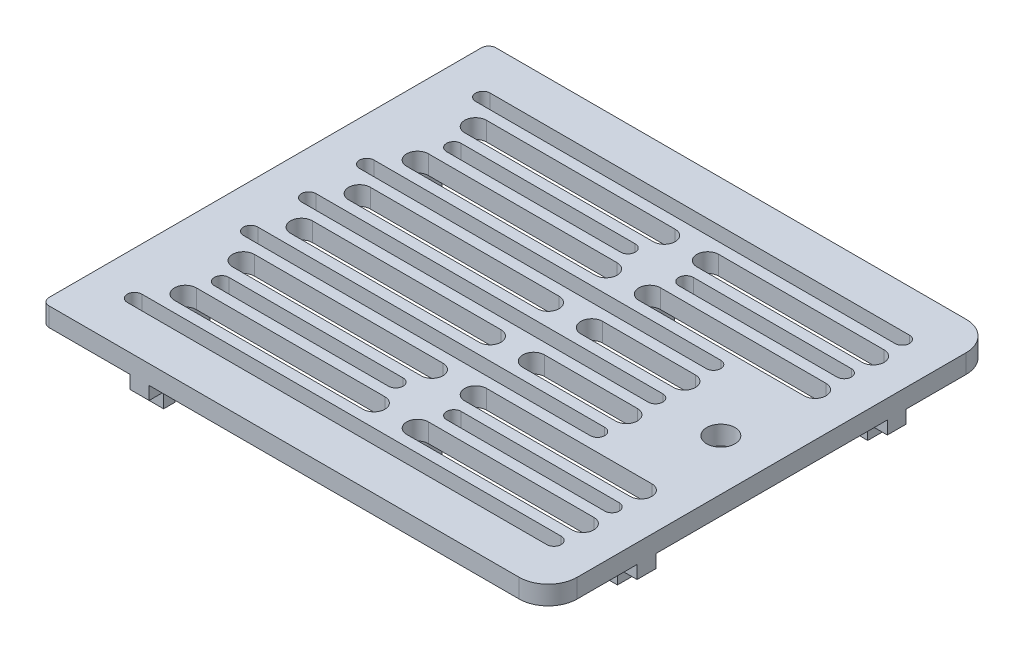
SolidWorks part; units mm, degrees
ref_plane "Front Plane" through (0, 0, 0) normal (0, 0, 1) x (1, 0, 0)
ref_plane "Top Plane" through (0, 0, 0) normal (0, 1, 0) x (1, 0, 0)
ref_plane "Right Plane" through (0, 0, 0) normal (1, 0, 0) x (0, 0, -1)
sketch "Sketch1" plane through (0, 0, 0) normal (0, 1, 0) x (1, 0, 0)
  line L1 (-33.9, -30.8) -> (30.9, -30.8)
  line L2 (-34.9, -29.8) -> (-34.9, 29.8)
  line L3 (-33.9, 30.8) -> (30.9, 30.8)
  line L4 (34.9, -26.8) -> (34.9, 26.8)
  line L5 (-34.9, -30.8) -> (34.9, 30.8) construction
  line L6 (-34.9, 30.8) -> (34.9, -30.8) construction
  arc A0 (30.9, -30.8) -> (34.9, -26.8) centre (30.9, -26.8) ccw
  arc A1 (34.9, 26.8) -> (30.9, 30.8) centre (30.9, 26.8) ccw
  arc A2 (-34.9, -29.8) -> (-33.9, -30.8) centre (-33.9, -29.8) ccw
  arc A3 (-33.9, 30.8) -> (-34.9, 29.8) centre (-33.9, 29.8) ccw
  point P0 (0, 0)
  dimension "D1" = 4
  dimension "D4" = 1
  dimension "D2" = 61.6
  dimension "D3" = 69.8
extrude "Boss-Extrude1" add sketch "Sketch1" along normal blind 2.6
sketch "Sketch3" plane through (0, 0, 0) normal (0, -1, 0) x (1, 0, 0)
  line L0 (-34.9, 0) -> (34.9, 0) construction
  line L1 (-28.9, -16) -> (3.1, -16) construction
  line L2 (-28.9, -16) -> (-28.9, 16) construction
  line L3 (-28.9, 16) -> (3.1, 16) construction
  line L4 (3.1, -16) -> (3.1, 16) construction
  line L5 (-28.9, -16) -> (3.1, 16) construction
  line L6 (-28.9, 16) -> (3.1, -16) construction
  line L7 (-34.9, -29.8) -> (-34.9, 29.8) construction
  line L8 (34.9, 26.8) -> (34.9, -26.8) construction
  circle A0 centre (-28.9, 16) radius 1.7
  circle A1 centre (3.1, 16) radius 1.7
  circle A2 centre (-28.9, -16) radius 1.7
  circle A3 centre (3.1, -16) radius 1.7
  circle A4 centre (3.1, 16) radius 0.75
  circle A5 centre (-28.9, 16) radius 0.75
  circle A6 centre (-28.9, -16) radius 0.75
  circle A7 centre (3.1, -16) radius 0.75
  point P14 (-12.9, 0)
  point P20 (0, 0)
  point P21 (-11.73, 0.4922)
  dimension "D2" = 3.4
  dimension "D3" = 1.5
  dimension "D1" = 32
  dimension "D4" = 6
extrude "Boss-Extrude2" add sketch "Sketch3" along normal blind 4.4
sketch "Sketch2" plane through (0, 2.6, 0) normal (0, 1, 0) x (1, 0, 0)
  line L0 (-34.9, -20) -> (34.9, -20) construction
  line L3 (-34.9, 29.8) -> (-34.9, -29.8) construction
  line L4 (34.9, -26.8) -> (34.9, 26.8) construction
  line L6 (-34.9, 0) -> (34.9, 0) construction
  line L9 (28.9, -20) -> (6.1, -20) construction
  line L10 (28.9, -21.5) -> (6.1, -21.5)
  line L11 (28.9, -18.5) -> (6.1, -18.5)
  line L12 (0.1, -20) -> (-25.9, -20) construction
  line L13 (0.1, -21.5) -> (-25.9, -21.5)
  line L14 (0.1, -18.5) -> (-25.9, -18.5)
  arc A2 (28.9, -21.5) -> (28.9, -18.5) centre (28.9, -20) ccw
  arc A3 (6.1, -18.5) -> (6.1, -21.5) centre (6.1, -20) ccw
  arc A4 (0.1, -21.5) -> (0.1, -18.5) centre (0.1, -20) ccw
  arc A5 (-25.9, -18.5) -> (-25.9, -21.5) centre (-25.9, -20) ccw
  circle A6 centre (-28.9, -16) radius 0.75 construction
  circle A7 centre (-28.9, -16) radius 0.75 construction
  circle A8 centre (3.1, -16) radius 0.75 construction
  point P6 (-26.515, -24)
  point P7 (6.7269, -24)
  point P10 (28.5523, -24)
  point P11 (6.1, -21.8921)
  point P15 (17.5, -20)
  point P22 (-12.9, -20)
  point P29 (0, 0)
  point P35 (3.9847, -24)
  point P38 (-12.9, 0)
  dimension "D1" = 4
  dimension "D6" = 1.5
  dimension "D2" = 3
  dimension "D3" = 3
  dimension "D4" = 6
  dimension "D5" = 6
extrude "Cut-Extrude1" cut sketch "Sketch2" against normal through all
pattern_linear "LPattern1" count 6 spacing 8 along (0, 0, -1) of "Cut-Extrude1"
sketch "Sketch4" plane through (0, 0, 0) normal (0, -1, 0) x (1, 0, 0)
  line L0 (-34.9, 24) -> (34.9, 24) construction
  line L1 (-34.9, -29.8) -> (-34.9, 29.8) construction
  line L2 (34.9, 26.8) -> (34.9, -26.8) construction
  line L3 (-28.9, 24) -> (28.9, 24) construction
  line L4 (-28.9, 25) -> (28.9, 25)
  line L5 (-28.9, 23) -> (28.9, 23)
  line L6 (-28.9, 16) -> (34.9, 16) construction
  line L7 (-24.9, 16) -> (-0.9, 16) construction
  line L8 (-24.9, 17) -> (-0.9, 17)
  line L9 (-24.9, 15) -> (-0.9, 15)
  line L10 (7.1, 16) -> (28.9, 16) construction
  line L11 (7.1, 17) -> (28.9, 17)
  line L12 (7.1, 15) -> (28.9, 15)
  line L13 (-28.9, -16) -> (34.9, -16) construction
  line L14 (-24.9, -16) -> (-0.9, -16) construction
  line L15 (-24.9, -15) -> (-0.9, -15)
  line L16 (-24.9, -17) -> (-0.9, -17)
  line L17 (7.1, -16) -> (28.9, -16) construction
  line L18 (7.1, -15) -> (28.9, -15)
  line L19 (7.1, -17) -> (28.9, -17)
  line L20 (-34.9, -24) -> (34.9, -24) construction
  line L21 (-28.9, -24) -> (28.9, -24) construction
  line L22 (-28.9, -23) -> (28.9, -23)
  line L23 (-28.9, -25) -> (28.9, -25)
  line L24 (-28.9, 24) -> (-28.9, -24) construction
  line L25 (28.9, 24) -> (28.9, -24) construction
  line L26 (-28.9, 8) -> (18.9, 8) construction
  line L27 (-28.9, 9) -> (18.9, 9)
  line L28 (-28.9, 7) -> (18.9, 7)
  line L29 (18.9, 0) -> (-28.9, 0) construction
  line L30 (18.9, -1) -> (-28.9, -1)
  line L31 (18.9, 1) -> (-28.9, 1)
  line L32 (-28.9, -8) -> (18.9, -8) construction
  line L33 (-28.9, -7) -> (18.9, -7)
  line L34 (-28.9, -9) -> (18.9, -9)
  arc A0 (-25.9, 21.5) -> (-25.9, 18.5) centre (-25.9, 20) ccw construction
  arc A1 (-28.9, 25) -> (-28.9, 23) centre (-28.9, 24) ccw
  arc A2 (28.9, 23) -> (28.9, 25) centre (28.9, 24) ccw
  arc A3 (-28.9, 9) -> (-28.9, 7) centre (-28.9, 8) ccw
  arc A4 (-24.9, 17) -> (-24.9, 15) centre (-24.9, 16) ccw
  arc A5 (-0.9, 15) -> (-0.9, 17) centre (-0.9, 16) ccw
  arc A6 (7.1, 17) -> (7.1, 15) centre (7.1, 16) ccw
  arc A7 (28.9, 15) -> (28.9, 17) centre (28.9, 16) ccw
  circle A8 centre (3.1, 16) radius 0.75 construction
  arc A9 (-24.9, -15) -> (-24.9, -17) centre (-24.9, -16) ccw
  arc A10 (-0.9, -17) -> (-0.9, -15) centre (-0.9, -16) ccw
  arc A11 (7.1, -15) -> (7.1, -17) centre (7.1, -16) ccw
  arc A12 (28.9, -17) -> (28.9, -15) centre (28.9, -16) ccw
  arc A13 (-28.9, -23) -> (-28.9, -25) centre (-28.9, -24) ccw
  arc A14 (28.9, -25) -> (28.9, -23) centre (28.9, -24) ccw
  arc A15 (-25.9, -18.5) -> (-25.9, -21.5) centre (-25.9, -20) ccw construction
  arc A16 (18.9, 7) -> (18.9, 9) centre (18.9, 8) ccw
  arc A17 (18.9, -1) -> (18.9, 1) centre (18.9, 0) ccw
  arc A18 (-28.9, 1) -> (-28.9, -1) centre (-28.9, 0) ccw
  arc A19 (-28.9, -7) -> (-28.9, -9) centre (-28.9, -8) ccw
  arc A20 (18.9, -9) -> (18.9, -7) centre (18.9, -8) ccw
  arc A21 (-25.9, 13.5) -> (-25.9, 10.5) centre (-25.9, 12) ccw construction
  arc A22 (-25.9, -10.5) -> (-25.9, -13.5) centre (-25.9, -12) ccw construction
  circle A23 centre (27.9, 0) radius 1.95
  point P11 (0, 24)
  point P22 (-12.9, 16)
  point P27 (18, 16)
  point P42 (-12.9, -16)
  point P47 (18, -16)
  point P56 (0, -24)
  point P72 (-5, 8)
  point P77 (-5, 0)
  point P84 (-5, -8)
  point P97 (0, 0)
  point P98 (28.9, 0)
  point P99 (18.4041, -8)
  point P100 (18.4041, 8)
  point P103 (-5, 0)
  dimension "D2" = 1
  dimension "D5" = 4
  dimension "D7" = 1
  dimension "D9" = 4
  dimension "D10" = 4
  dimension "D11" = 3.9
  dimension "D1" = 4
  dimension "D3" = 6
  dimension "D4" = 4
  dimension "D6" = 4
  dimension "D8" = 4
  dimension "D12" = 9
  dimension "D13" = 1
extrude "Cut-Extrude2" cut sketch "Sketch4" against normal through all
sketch "Sketch6" plane through (0, 0, 0) normal (0, -1, 0) x (1, 0, 0)
  line L0 (-22.7, 27.2) -> (-22.7, -27.2) construction
  line L1 (-22.7, 30.8) -> (-20.1, 30.8)
  line L2 (-22.7, 30.8) -> (-22.7, 27.2)
  line L3 (-22.7, 27.2) -> (-20.1, 27.2)
  line L4 (-20.1, 30.8) -> (-20.1, 27.2)
  line L5 (-22.7, -27.2) -> (-20.1, -27.2)
  line L6 (-22.7, -27.2) -> (-22.7, -30.8)
  line L7 (-22.7, -30.8) -> (-20.1, -30.8)
  line L8 (-20.1, -27.2) -> (-20.1, -30.8)
  line L9 (34.9, 18.55) -> (30.6, 18.55)
  line L10 (34.9, 18.55) -> (34.9, 15.95)
  line L11 (34.9, 15.95) -> (30.6, 15.95)
  line L12 (30.6, 18.55) -> (30.6, 15.95)
  line L13 (34.9, -15.95) -> (30.6, -15.95)
  line L14 (34.9, -15.95) -> (34.9, -18.55)
  line L15 (34.9, -18.55) -> (30.6, -18.55)
  line L16 (30.6, -15.95) -> (30.6, -18.55)
  line L17 (-34.9, 0) -> (34.9, 0) construction
  line L18 (-34.9, -29.8) -> (-34.9, 29.8) construction
  line L20 (-33.9, 30.8) -> (30.9, 30.8) construction
  line L21 (30.9, -30.8) -> (-33.9, -30.8) construction
  line L22 (34.9, 26.8) -> (34.9, -26.8) construction
  line L23 (34.9, 26.8) -> (34.9, -26.8) construction
  line L24 (30.6, 15.95) -> (30.6, -15.95) construction
  point P22 (-22.7, 0)
  point P23 (30.6, 0)
  point P24 (0, 0)
  dimension "D1" = 54.4
  dimension "D2" = 2.6
  dimension "D3" = 12.2
  dimension "D4" = 31.9
  dimension "D5" = 4.3
extrude "Boss-Extrude4" add sketch "Sketch6" along normal blind 1.8
sketch "Sketch7" plane through (0, -1.8, 0) normal (0, -1, 0) x (1, 0, 0)
  line L0 (-20.1, 27.2) -> (-20.1, 30.8) construction
  line L1 (-22.7, 27.2) -> (-20.1, 27.2)
  line L2 (-22.7, 27.2) -> (-22.7, 28.8)
  line L3 (-22.7, 28.8) -> (-20.1, 28.8)
  line L4 (-20.1, 27.2) -> (-20.1, 28.8)
  line L5 (30.6, 15.95) -> (34.9, 15.95) construction
  line L6 (30.6, 18.55) -> (32.2, 18.55)
  line L7 (30.6, 18.55) -> (30.6, 15.95)
  line L8 (30.6, 15.95) -> (32.2, 15.95)
  line L9 (32.2, 18.55) -> (32.2, 15.95)
  line L10 (30.6, -18.55) -> (34.9, -18.55) construction
  line L11 (30.6, -15.95) -> (32.2, -15.95)
  line L12 (30.6, -15.95) -> (30.6, -18.55)
  line L13 (30.6, -18.55) -> (32.2, -18.55)
  line L14 (32.2, -15.95) -> (32.2, -18.55)
  line L16 (-20.1, -27.2) -> (-22.7, -27.2)
  line L17 (-20.1, -27.2) -> (-20.1, -28.8)
  line L18 (-20.1, -28.8) -> (-22.7, -28.8)
  line L19 (-22.7, -27.2) -> (-22.7, -28.8)
  line L20 (-22.7, -27.2) -> (-22.7, -30.8) construction
  point P26 (-22.7, -28.1642)
  dimension "D1" = 1.6
extrude "Boss-Extrude5" add sketch "Sketch7" along normal blind 2
sketch "Sketch8" plane through (0, 0, 0) normal (0, -1, 0) x (1, 0, 0)
  line L0 (28.9, -5.5) -> (6.1, -5.5) construction
  line L1 (6.1, -2.5) -> (28.9, -2.5) construction
  line L2 (28.9, 2.5) -> (6.1, 2.5) construction
  line L3 (6.1, 5.5) -> (28.9, 5.5) construction
  line L4 (28.9, -5.5) -> (18.9, -5.5)
  line L5 (18.9, -2.5) -> (28.9, -2.5)
  line L6 (28.9, 2.5) -> (18.9, 2.5)
  line L7 (18.9, 5.5) -> (28.9, 5.5)
  arc A0 (28.9, -5.5) -> (28.9, -2.5) centre (28.9, -4) ccw construction
  arc A1 (28.9, 2.5) -> (28.9, 5.5) centre (28.9, 4) ccw construction
  arc A2 (28.9, -5.5) -> (28.9, -2.5) centre (28.9, -4) ccw
  arc A3 (28.9, 2.5) -> (28.9, 5.5) centre (28.9, 4) ccw
  arc A4 (18.9, 5.5) -> (18.9, 2.5) centre (18.9, 4) cw
  arc A5 (18.9, -2.5) -> (18.9, -5.5) centre (18.9, -4) cw
  point P16 (23.1618, 2.5)
  point P17 (0, 0)
  point P18 (0, 0)
extrude "Boss-Extrude6" add sketch "Sketch8" against normal up to surface (2.6 mm away) up to face at (0, 2.6, 24)
sketch "Sketch9" plane through (0, 0, 0) normal (0, -1, 0) x (1, 0, 0)
  circle A0 centre (27.9, 0) radius 1.95 construction
  circle A1 centre (27.9, 0) radius 4.3
  circle A2 centre (27.9, 0) radius 6.15 construction
  circle A3 centre (27.9, 0) radius 8.5
  point P4 (27.9, 0)
  point P7 (28.6725, -0.6455)
  dimension "D1" = 8.6
  dimension "D2" = 12.3
  dimension "D3" = 17
extrude "Boss-Extrude7" add sketch "Sketch9" along normal blind 4
sketch "Sketch12" plane through (0, -4, 0) normal (0, -1, 0) x (1, 0, 0)
  line L0 (27.9, 6.15) -> (27.9, -6.15) construction
  circle A0 centre (27.9, 0) radius 1.95 construction
  circle A1 centre (27.9, 6.15) radius 0.95
  circle A2 centre (27.9, -6.15) radius 0.95
  point P4 (27.9, 0)
  dimension "D2" = 1.9
  dimension "D1" = 12.3
extrude "Cut-Extrude3" cut sketch "Sketch12" against normal up to surface (4 mm away) up to face at (7.9878, 0, 0)
sketch "Sketch13" plane through (0, -4, 0) normal (0, -1, 0) x (1, 0, 0)
  line L1 (42.3525, 9.3129) -> (30.9, 9.3129)
  line L2 (42.3525, 9.3129) -> (42.3525, -9.242)
  line L3 (42.3525, -9.242) -> (30.9, -9.242)
  line L4 (30.9, 9.3129) -> (30.9, -9.242)
  line L6 (24.9, 10.901) -> (9.8194, 10.901)
  line L7 (24.9, 10.901) -> (24.9, -10.1427)
  line L8 (24.9, -10.1427) -> (9.8194, -10.1427)
  line L9 (9.8194, 10.901) -> (9.8194, -10.1427)
  circle A0 centre (27.9, 0) radius 1.95 construction
  point P4 (42.3525, 9.3129)
  point P5 (9.8194, 10.901)
  dimension "D1" = 3
  dimension "D2" = 3
extrude "Cut-Extrude4" cut sketch "Sketch13" against normal up to surface (4 mm away) up to face at (7.9878, 0, 0)
fillet "Fillet1" radius 1 4 edges at (24.9, -2, -3.0806) (24.9, -2, 3.0806) (30.9, -2, 3.0806) (30.9, -2, -3.0806)
fillet "Fillet2" radius 1 4 edges at (30.9, -2, -7.953) (30.9, -2, 7.953) (24.9, -2, -7.953) (24.9, -2, 7.953)
